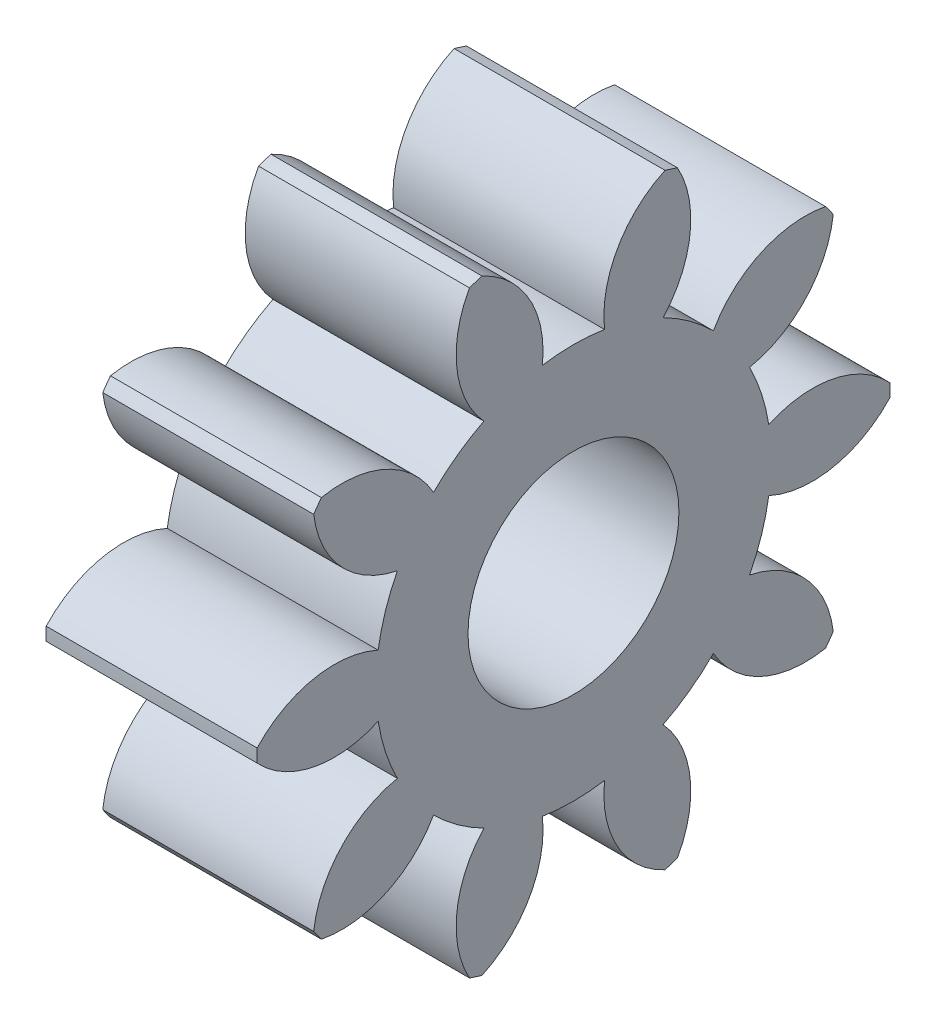
SolidWorks part; units mm, degrees
ref_plane "Plane1" through (0, 0, 0) normal (0, 0, 1) x (1, 0, 0)
ref_plane "Plane2" through (0, 0, 0) normal (0, 1, 0) x (1, 0, 0)
ref_plane "Plane3" through (0, 0, 0) normal (1, 0, 0) x (0, 0, -1)
sketch "HoldingSke" plane through (0, 0, 0) normal (0, 1, 0) x (1, 0, 0)
  line L0 (0, 0) -> (0.6565, -0.1158)
  line L1 (-15, 0) -> (100, 0) construction
  line L2 (0, 0) -> (-2.1039, 2.3779)
  line L3 (0, 0) -> (-11.863, 4.5341)
  line L4 (0, 0) -> (8.5048, 1.4996)
  line L5 (0, 0) -> (-46.8476, -17.4728)
  line L6 (0, 0) -> (-9.9476, -6.7116)
  line L7 (-2.1039, 2.3779) -> (8.6586, 51.2059)
  line L8 (-76.2, 54.61) -> (-76.1, 54.61)
  line L9 (-71.009, 38.7566) -> (-53.1078, 45.2721)
  line L10 (-76.2, 71.12) -> (104.1128, 71.12)
  line L11 (0, 0) -> (-12, 0)
  line L12 (-76.2, 101.6) -> (-76.147, 101.6)
  line L13 (24.9733, 27.94) -> (52.9518, 28.4284)
  line L14 (24.9733, 27.94) -> (24.9743, 27.94)
  line L15 (24.9733, 27.94) -> (100.4006, 29.5858)
  line L16 (-63.627, -1.5) -> (-12.827, -1.5)
  circle A0 centre (0, 0) radius 0.4
  circle A1 centre (0, 0) radius 5.624
  circle A2 centre (0, 0) radius 37.5
  circle A3 centre (0, 0) radius 0.4
  dimension "MHD" = 11.248
  dimension "Hub_dia" = 75
  dimension "Bore" = 0.8
  dimension "MBD" = 0.8
  dimension "Num_teeth" = 10
  dimension "Pitch_radius" = 180.3128
  dimension "Pitch" = 0.6667
  dimension "Width" = 12
  dimension "Overall_len" = 50
  dimension "Show_teeth" = 10
  dimension "Thickness" = 12
  dimension "OAL" = 50.0001
  dimension "T_dim" = 0.1
  dimension "Ap" = 20
  dimension "H" = 19.05
  dimension "Backlash" = 0.053
  dimension "Addendum_fac" = 1
  dimension "Dedendum_fac" = 1.25
  dimension "Clearance_fac" = 0.25
  dimension "Dedendum_add" = 0.001
  dimension "Module" = 1.5
sketch "BasProSke" plane through (0, 0, 0) normal (0, 1, 0) x (1, 0, 0)
  line L0 (-10, 0) -> (60, 0) construction
  line L1 (0, 0) -> (0, 9)
  line L2 (0, 0) -> (12, 0)
  line L3 (12, 0) -> (12, 9)
  line L4 (12, 9) -> (0, 9)
  dimension "Diameter" = 18
  dimension "Thickness" = 12
revolve "Base-Revolve" add sketch "BasProSke" angle 360 about L0
sketch "TooCutSke" plane through (0, 0, 0) normal (1, 0, 0) x (0, 0, -1)
  line L1 (0, 0) -> (0, 107) construction
  line L2 (0, 0) -> (-1.2658, 7.3924) construction
  line L3 (0, 0) -> (-4.5869, 14.117) construction
  line L4 (-1.2658, 7.3924) -> (-2.2934, 7.0585) construction
  arc A0 (0.8839, 5.5541) -> (-0.8839, 5.5541) centre (0, 0) ccw
  arc A1 (2.6378, 8.6313) -> (-2.6378, 8.6313) centre (0, 0) ccw
  circle A2 centre (0, 0) radius 7.5 construction
  circle A3 centre (0, 0) radius 7.0477 construction
  arc A4 (-0.8839, 5.5541) -> (-2.6378, 8.6313) centre (-3.8646, 5.8936) ccw
  arc A5 (2.6378, 8.6313) -> (0.8839, 5.5541) centre (3.8646, 5.8936) ccw
  dimension "Root_dia" = 11.248
  dimension "Overcut_dia" = 18.0508
  dimension "Pitch_dia" = 15
  dimension "Base_dia" = 14.0954
  dimension "Flank_rad" = 3
  dimension "Half_ang" = 18
  dimension "Half_CT" = 1.0805
extrude "ToothCut" cut sketch "TooCutSke" along normal through all
fillet "Breaks" [suppressed] radius 0.03
fillet "RootFillets" [suppressed] radius 0.376
pattern_circular "TeethCuts" count 10 every 36 about axis through (-10, 0, 0) along (1, 0, 0) of "ToothCut", "RootFillets", "Breaks"
sketch "HubNeaOneSke" plane through (0, 0, 0) normal (-1, 0, 0) x (0, 0, 1)
  circle A0 centre (0, 0) radius 5.624
  dimension "Diameter" = 11.248
extrude "HubNearOne" [suppressed] add sketch "HubNeaOneSke" along normal blind 38.0001
sketch "HubNeaBotSke" plane through (0, 0, 0) normal (-1, 0, 0) x (0, 0, 1)
  circle A0 centre (0, 0) radius 5.624
  dimension "Diameter" = 11.248
extrude "HubNearBoth" [suppressed] add sketch "HubNeaBotSke" along normal blind 19
ref_plane "FarPln" through (12, 0, 0) normal (1, 0, 0) x (0, 0, -1)
sketch "HubFarSke" plane through (12, 0, 0) normal (1, 0, 0) x (0, 0, -1)
  circle A0 centre (0, 0) radius 5.624
  dimension "Diameter" = 11.248
extrude "HubFar" [suppressed] add sketch "HubFarSke" along normal blind 19
sketch "BorSke" plane through (0, 0, 0) normal (1, 0, 0) x (0, 0, -1)
  circle A0 centre (0, 0) radius 0.4
  dimension "Diameter" = 0.8
extrude "Bore" cut sketch "BorSke" along normal mid plane 100.0001
sketch "KeySke" plane through (0, 0, 0) normal (1, 0, 0) x (0, 0, -1)
  line L0 (-0.05, 0) -> (-0.05, 0.5)
  line L1 (-0.05, 0.5) -> (0.05, 0.5)
  line L2 (0.05, 0.5) -> (0.05, 0)
  line L3 (0, 0) -> (0, 34) construction
  line L4 (-0.05, 0) -> (0.05, 0)
  dimension "Offset" = 0.5
  dimension "Width" = 0.1
extrude "Keyway" [suppressed] cut sketch "KeySke" along normal mid plane 100.0001
pattern_circular "Keyway2" [suppressed] count 2 every 90 about axis through (-10, 0, 0) along (1, 0, 0)
sketch "Sketch1" plane through (0, 0, 0) normal (-1, 0, 0) x (0, 0, 1)
  circle A0 centre (0, 0) radius 3
  circle M41 centre (0, 0) radius 0.4
  dimension "D1" = 6
extrude "Cut-Extrude2" cut sketch "Sketch1" against normal through all contours A0 M41
fillet "Fillet1" [suppressed] radius 0.5
sketch "Sketch2" plane through (12, 0, 0) normal (1, 0, 0) x (0, 0, -1)
  circle A0 centre (0, 0) radius 20.4408
extrude "Cut-Extrude3" cut sketch "Sketch2" against normal offset from surface (6 mm away) 6 up to face at (0, 0, 3)
equation "' \"Module@HoldingSke\" = 6.35"
equation "' \"Num_teeth@HoldingSke\" = 12"
equation "' \"Ap@HoldingSke\" =  20"
equation "' \"Width@HoldingSke\" = 0.5 * 25.4"
equation "' \"Hub_dia@HoldingSke\"= 1 * 25.4"
equation "' \"Overall_len@HoldingSke\" = 1.0 * 25.4"
equation "' \"Bore@HoldingSke\" = 0.75 * 25.4"
equation "' \"T_dim@HoldingSke\" = 0.1 * 25.4"
equation "' \"Width@KeySke\" = 0.25 * 25.4"
equation "' \"Show_teeth@HoldingSke\" = 13"
equation "' \"Backlash@HoldingSke\" = 0.009 * 25.4"
equation "' \"Addendum_fac@HoldingSke\" = 1.0"
equation "' \"Dedendum_fac@HoldingSke\" = 1.25"
equation "' \"Dedendum_add@HoldingSke\" = 0.00005 * 25.4"
equation "' \"Clearance_fac@HoldingSke\" = 0.25"
equation "\"Pitch@HoldingSke\" = 1 / \"Module@HoldingSke\""
equation "\"Overcut_dia@TooCutSke\" = (\"Num_teeth@HoldingSke\" + 2 * \"Addendum_fac@HoldingSke\") / \"Pitch@HoldingSke\" + 0.002 * 25.4"
equation "\"Pitch_dia@TooCutSke\" = \"Num_teeth@HoldingSke\" / \"Pitch@HoldingSke\""
equation "\"Base_dia@TooCutSke\" = \"Num_teeth@HoldingSke\" / \"Pitch@HoldingSke\" * cos((\"Ap@HoldingSke\"  * 3.14159265 / 180))"
equation "\"Root_dia@TooCutSke\" = (\"Num_teeth@HoldingSke\" + 2) / \"Pitch@HoldingSke\" - 2 * (\"Addendum_fac@HoldingSke\" + \"Dedendum_fac@HoldingSke\") / \"Pitch@HoldingSke\" - \"Dedendum_add@HoldingSke\" * 2"
equation "\"Half_ang@TooCutSke\" = 180 / \"Num_teeth@HoldingSke\""
equation "\"Half_CT@TooCutSke\" = \"Num_teeth@HoldingSke\" / \"Pitch@HoldingSke\" * sin((3.14159265 / 2 / \"Num_teeth@HoldingSke\")) / 2 - 7 * \"Backlash@HoldingSke\" / 4"
equation "\"Flank_rad@TooCutSke\" = \"Num_teeth@HoldingSke\" / \"Pitch@HoldingSke\" / 5"
equation "\"Radius@RootFillets\" = \"Clearance_fac@HoldingSke\" / \"Pitch@HoldingSke\" + \"Dedendum_add@HoldingSke\""
equation "\"Break_rad@Breaks\" = 0.02 / \"Pitch@HoldingSke\""
equation "\"Thickness@HoldingSke\" = \"Width@HoldingSke\""
equation "\"OAL@HoldingSke\" = \"Thickness@HoldingSke\""
equation "\"MHD@HoldingSke\" = (\"Num_teeth@HoldingSke\" + 2) / \"Pitch@HoldingSke\" - 2 * (\"Addendum_fac@HoldingSke\" + \"Dedendum_fac@HoldingSke\")  / \"Pitch@HoldingSke\" - \"Dedendum_add@HoldingSke\" * 2"
equation "\"MBD@HoldingSke\" = (\"Num_teeth@HoldingSke\" + 2) / \"Pitch@HoldingSke\" - 2 * (\"Addendum_fac@HoldingSke\" + \"Dedendum_fac@HoldingSke\")  / \"Pitch@HoldingSke\" - \"Dedendum_add@HoldingSke\" * 2 - 0.002 * 25.4"
equation "\"MHD@HoldingSke\" = ((sgn( \"MHD@HoldingSke\" - \"Hub_dia@HoldingSke\" )-1)*( \"MHD@HoldingSke\" - \"Hub_dia@HoldingSke\" ))/-2+ \"Hub_dia@HoldingSke\""
equation "\"MBD@HoldingSke\" = ((sgn( \"MBD@HoldingSke\" - \"Bore@HoldingSke\" )-1)*( \"MBD@HoldingSke\" - \"Bore@HoldingSke\" ))/-2+ \"Bore@HoldingSke\""
equation "\"OAL@HoldingSke\" = ((sgn( \"OAL@HoldingSke\" - \"Overall_len@HoldingSke\" )+1)*( \"OAL@HoldingSke\" - \"Overall_len@HoldingSke\" ))/2 + \"Overall_len@HoldingSke\" + 0.000002 * 25.4"
equation "\"Num_teeth@TeethCuts\" = int( \"Show_teeth@HoldingSke\" ) + 1"
equation "\"Num_teeth@TeethCuts\" = ((sgn( \"Num_teeth@TeethCuts\" - \"Num_teeth@HoldingSke\" )-1)*( \"Num_teeth@TeethCuts\" - \"Num_teeth@HoldingSke\" ))/-2+ \"Num_teeth@HoldingSke\""
equation "\"Num_teeth@TeethCuts\" = ((sgn( \"Num_teeth@TeethCuts\" - 2.0)+1)*( \"Num_teeth@TeethCuts\" - 2.0))/2 +2.0"
equation "\"Angle@TeethCuts\" = 360.0 / \"Num_teeth@HoldingSke\""
equation "\"Diameter@BasProSke\" = (\"Num_teeth@HoldingSke\" + 2 * \"Addendum_fac@HoldingSke\") / \"Pitch@HoldingSke\""
equation "\"Thickness@BasProSke\"  = \"Thickness@HoldingSke\""
equation "' \"Fillet_rad@BasProSke\" =  \"Thickness@HoldingSke\" * 0.05"
equation "\"MHD@HoldingSke\" = ((sgn( \"MHD@HoldingSke\" - \"Root_dia@TooCutSke\" )-1)*( \"MHD@HoldingSke\" - \"Root_dia@TooCutSke\" ))/-2+ \"Root_dia@TooCutSke\""
equation "\"Diameter@HubNeaOneSke\" = \"MHD@HoldingSke\""
equation "\"Length@HubNearOne\" = \"OAL@HoldingSke\" - \"Thickness@BasProSke\""
equation "\"Diameter@HubNeaBotSke\" = \"MHD@HoldingSke\""
equation "\"Length@HubNearBoth\" = ( \"OAL@HoldingSke\" - \"Thickness@BasProSke\" ) / 2.0"
equation "\"Thickness@FarPln\" = \"Thickness@BasProSke\""
equation "\"Diameter@HubFarSke\" = \"MHD@HoldingSke\""
equation "\"Length@HubFar\" = ( \"OAL@HoldingSke\" - \"Thickness@BasProSke\" ) / 2.0"
equation "\"Diameter@BorSke\" = \"MBD@HoldingSke\""
equation "\"D1@Bore\" = \"OAL@HoldingSke\" * 2.0"
equation "\"D1@Keyway\" = \"OAL@HoldingSke\" * 2.0"
equation "\"Offset@KeySke\" = \"T_dim@HoldingSke\" + \"MBD@HoldingSke\" / 2.0"
